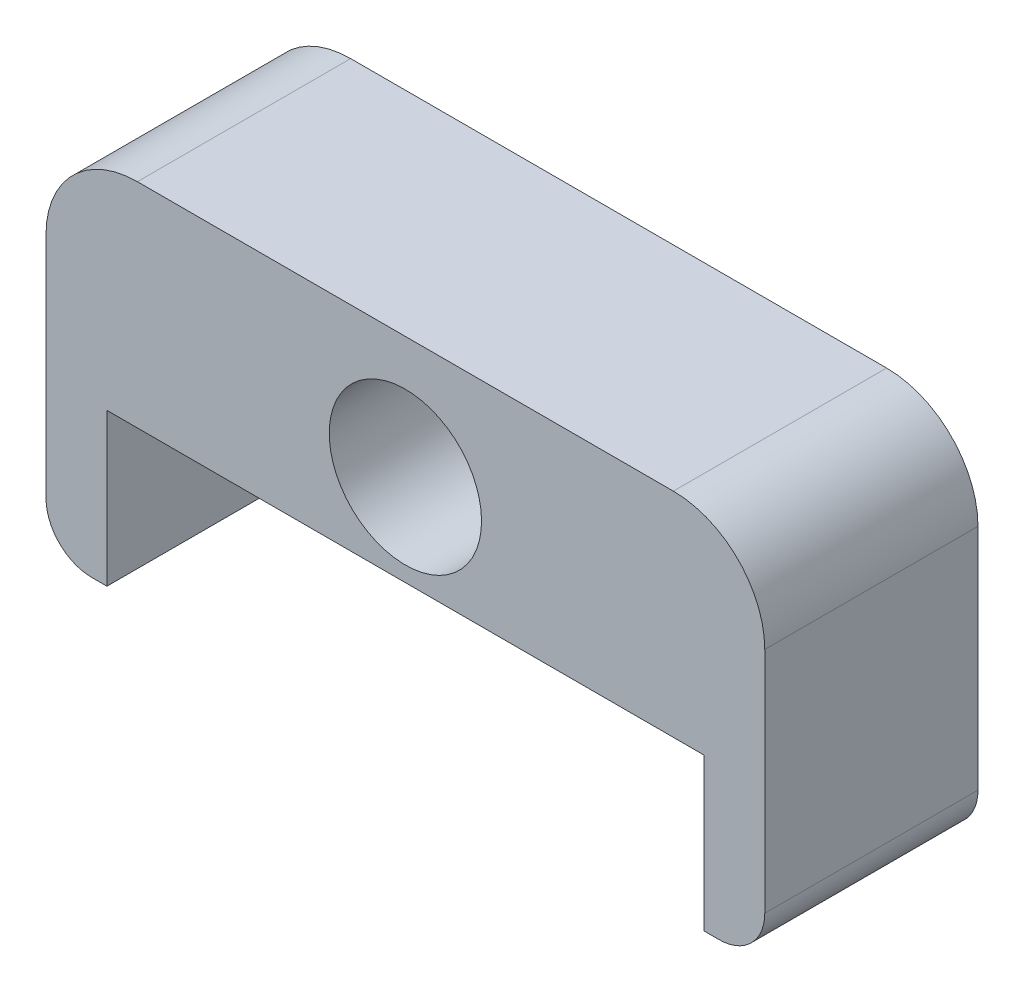
SolidWorks part; units mm, degrees
ref_plane "Front Plane" through (0, 0, 0) normal (0, 0, 1) x (1, 0, 0)
ref_plane "Top Plane" through (0, 0, 0) normal (0, 1, 0) x (1, 0, 0)
ref_plane "Right Plane" through (0, 0, 0) normal (1, 0, 0) x (0, 0, -1)
sketch "Sketch1" plane through (0, 0, 0) normal (0, 0, 1) x (1, 0, 0)
  line L0 (9.7967, 0) -> (-9.7967, 0)
  line L1 (-9.7967, 0) -> (-9.7967, -5)
  line L2 (-9.7967, -5) -> (-11.7967, -5)
  line L3 (-11.7967, -5) -> (-11.7967, 7)
  line L4 (-11.7967, 7) -> (11.7967, 7)
  line L5 (0, 7) -> (0, 0) construction
  line L6 (11.7967, -5) -> (11.7967, 7)
  line L7 (9.7967, -5) -> (11.7967, -5)
  line L8 (9.7967, 0) -> (9.7967, -5)
  dimension "D1" = 9.7967
  dimension "D2" = 2
  dimension "D3" = 7
  dimension "D4" = 5
extrude "Boss-Extrude1" add sketch "Sketch1" against normal blind 7
sketch "Sketch5" plane through (0, 0, 0) normal (0, 0, 1) x (1, 0, 0)
  line L0 (-9.7967, 0) -> (9.7967, 0) construction
  circle A1 centre (0, 3) radius 2.5
  dimension "D1" = 5
  dimension "D2" = 3
extrude "Cut-Extrude2" cut sketch "Sketch5" against normal through all
fillet "Fillet1" radius 3 1 edges at (11.7967, 7, -3.5)
fillet "Fillet2" radius 3 1 edges at (-11.7967, 7, -3.5)
fillet "Fillet3" radius 1.5 1 edges at (11.7967, -5, -3.5)
fillet "Fillet4" radius 1.5 1 edges at (-11.7967, -5, -3.5)
equation "\"LA_width\"=19.59343046"
equation "\"D1@Sketch1\"=\"LA_width\"/2"
equation "\"LA_height\"=28.33511482"
equation "\"LA_length\"=104.84505691"
equation "\"radius_pin\"=9.79671523"
